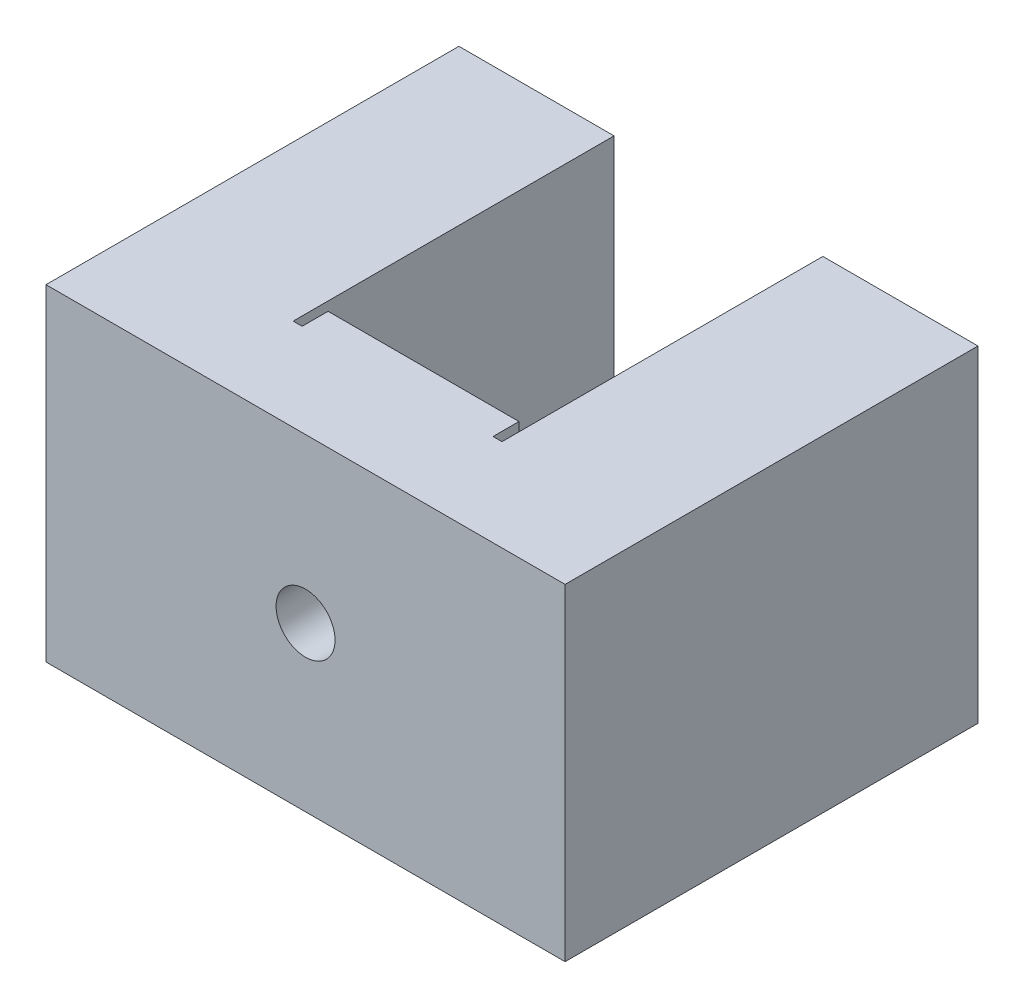
SolidWorks part; units mm, degrees
ref_plane "Front Plane" through (0, 0, 0) normal (0, 0, 1) x (1, 0, 0)
ref_plane "Top Plane" through (0, 0, 0) normal (0, 1, 0) x (1, 0, 0)
ref_plane "Right Plane" through (0, 0, 0) normal (1, 0, 0) x (0, 0, -1)
sketch "Sketch1" plane through (0, 0, 0) normal (0, 0, 1) x (1, 0, 0)
  line L1 (22, 13.85) -> (-22, 13.85)
  line L2 (22, 13.85) -> (22, -13.85)
  line L3 (22, -13.85) -> (-22, -13.85)
  line L4 (-22, 13.85) -> (-22, -13.85)
  line L5 (22, 13.85) -> (-22, -13.85) construction
  line L6 (22, -13.85) -> (-22, 13.85) construction
  point P0 (0, 0)
  dimension "D1" = 44
  dimension "D2" = 27.7
extrude "Boss-Extrude1" add sketch "Sketch1" along normal blind 10
sketch "Sketch2" plane through (0, 0, 0) normal (0, 0, -1) x (-1, 0, 0)
  line L0 (22, -13.85) -> (-22, -13.85) construction
  line L1 (8.85, 13.85) -> (-8.85, 13.85)
  line L2 (8.85, 13.85) -> (8.85, -13.85)
  line L3 (8.85, -13.85) -> (-8.85, -13.85)
  line L4 (-8.85, 13.85) -> (-8.85, -13.85)
  line L5 (8.85, 13.85) -> (-8.85, -13.85) construction
  line L6 (8.85, -13.85) -> (-8.85, 13.85) construction
  line L8 (22, -13.85) -> (-22, -13.85)
  line L9 (22, -13.85) -> (22, 13.85)
  line L10 (22, 13.85) -> (-22, 13.85)
  line L11 (-22, -13.85) -> (-22, 13.85)
  line L12 (22, -13.85) -> (-22, 13.85) construction
  line L13 (22, 13.85) -> (-22, -13.85) construction
  point P0 (0, 0)
  point P8 (0, 0)
  line M2 (22, -13.85) -> (22, 13.85)
  line M3 (22, 13.85) -> (-22, 13.85)
  line M4 (-22, 13.85) -> (-22, -13.85)
  line M5 (-22, -13.85) -> (22, -13.85)
  dimension "D1" = 17.7
extrude "Boss-Extrude2" add sketch "Sketch2" along normal blind 25 contours L4 M3 M4 M5 | L2 M3 M5 M2
sketch "Sketch3" plane through (0, 0, 10) normal (0, 0, 1) x (1, 0, 0)
  circle A0 centre (0, 0) radius 2.5
  dimension "D1" = 5
extrude "Cut-Extrude1" cut sketch "Sketch3" against normal blind 10
sketch "Sketch4" plane through (0, 0, 0) normal (0, 0, -1) x (-1, 0, 0)
  line L1 (8.85, -13.85) -> (-8.85, -13.85)
  line L2 (8.85, -13.85) -> (8.85, 13.85)
  line L3 (8.85, 13.85) -> (-8.85, 13.85)
  line L4 (-8.85, -13.85) -> (-8.85, 13.85)
  line L5 (8.85, -13.85) -> (-8.85, 13.85) construction
  line L6 (8.85, 13.85) -> (-8.85, -13.85) construction
  line L7 (8.09, -13.85) -> (-8.09, -13.85)
  line L8 (8.09, -13.85) -> (8.09, 13.85)
  line L9 (8.09, 13.85) -> (-8.09, 13.85)
  line L10 (-8.09, -13.85) -> (-8.09, 13.85)
  line L11 (8.09, -13.85) -> (-8.09, 13.85) construction
  line L12 (8.09, 13.85) -> (-8.09, -13.85) construction
  point P0 (0, 0)
  point P7 (0, 0)
  line M4 (-8.85, -13.85) -> (8.85, -13.85)
  line M5 (8.85, -13.85) -> (8.85, 13.85)
  line M6 (8.85, 13.85) -> (-8.85, 13.85)
  line M7 (-8.85, 13.85) -> (-8.85, -13.85)
  dimension "D1" = 0.76
extrude "Cut-Extrude2" cut sketch "Sketch4" against normal blind 2.2 contours L10 M4 M6 M7 | L8 M4 M5 M6
